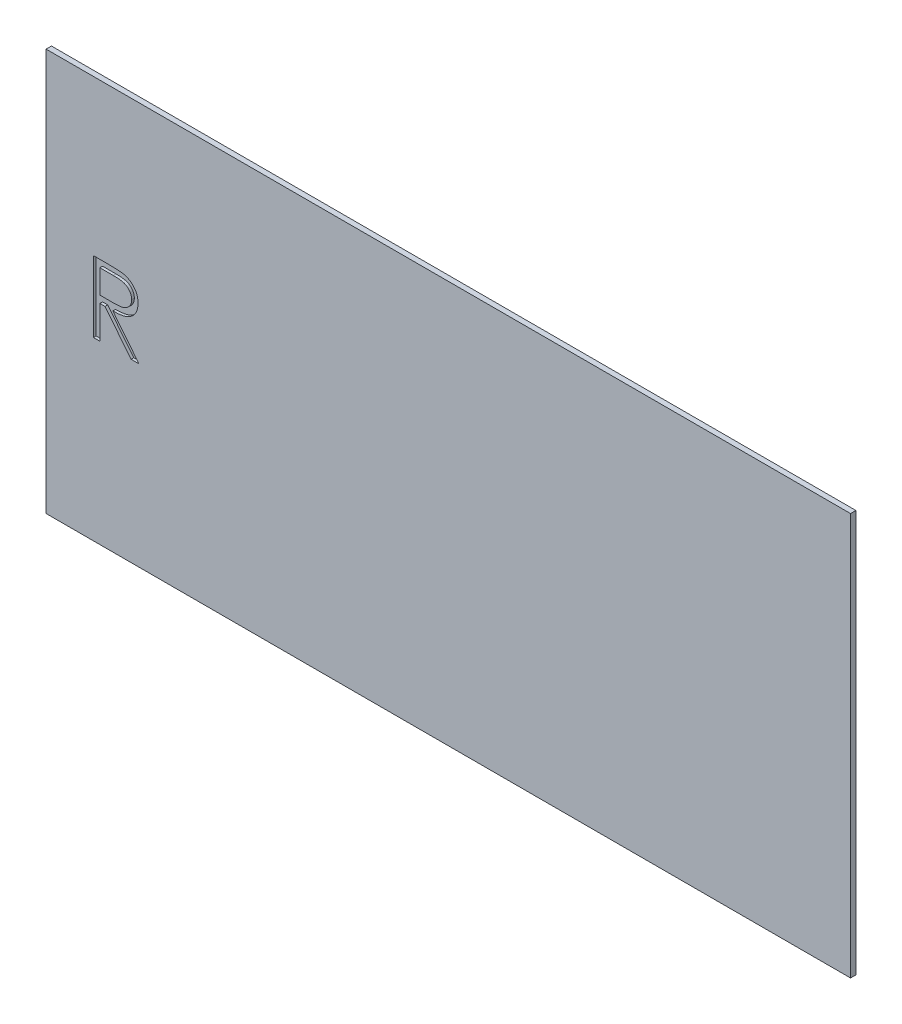
SolidWorks part; units mm, degrees
ref_plane "Front Plane" through (0, 0, 0) normal (0, 0, 1) x (1, 0, 0)
ref_plane "Top Plane" through (0, 0, 0) normal (0, 1, 0) x (1, 0, 0)
ref_plane "Right Plane" through (0, 0, 0) normal (1, 0, 0) x (0, 0, -1)
sketch "Sketch1" plane through (0, 0, 0) normal (0, 0, 1) x (1, 0, 0)
  line L1 (0, 0) -> (1500, 0)
  line L2 (0, 0) -> (0, 750)
  line L3 (0, 750) -> (1500, 750)
  line L4 (1500, 0) -> (1500, 750)
  dimension "D1" = 750
  dimension "D2" = 1500
extrude "Boss-Extrude1" add sketch "Sketch1" along normal blind 10
sketch "Sketch2" plane through (0, 0, 10) normal (0, 0, 1) x (1, 0, 0)
  text T0 "R" font "Century Gothic" height in points 500
extrude "Cut-Extrude1" cut sketch "Sketch2" against normal blind 5
